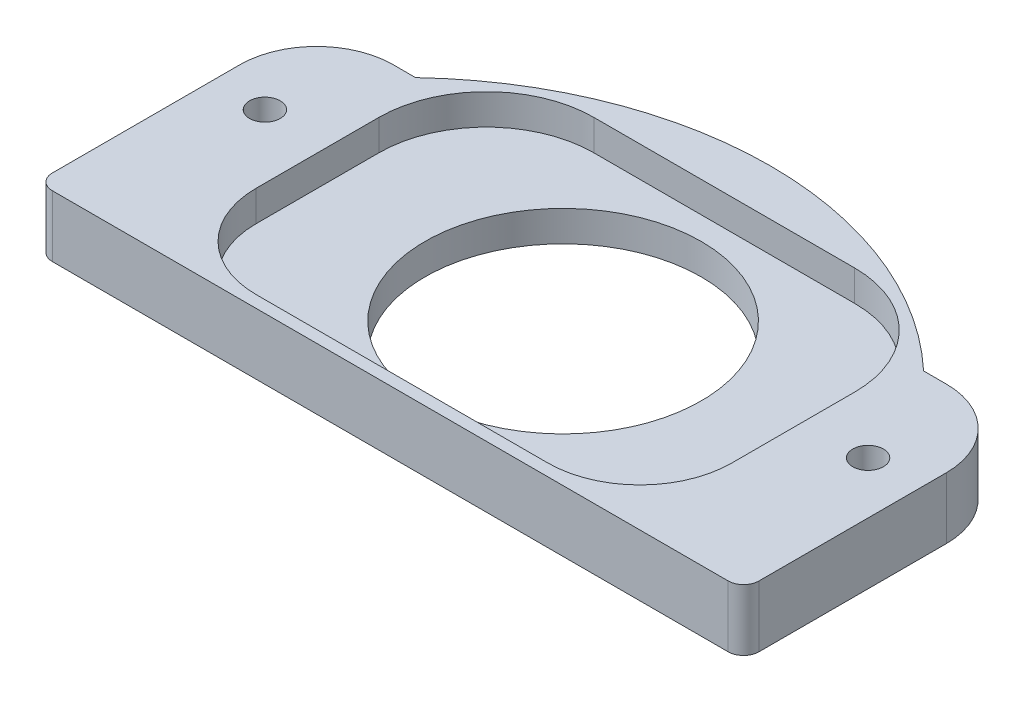
SolidWorks part; units mm, degrees
ref_plane "Front Plane" through (0, 0, 0) normal (0, 0, 1) x (1, 0, 0)
ref_plane "Top Plane" through (0, 0, 0) normal (0, 1, 0) x (1, 0, 0)
ref_plane "Right Plane" through (0, 0, 0) normal (1, 0, 0) x (0, 0, -1)
sketch "Sketch1" plane through (0, 0, 0) normal (0, 1, 0) x (1, 0, 0)
  line L0 (16.5494, 5.7) -> (18.0377, 5.7)
  line L2 (-23, 0.7) -> (-23, -11.5148)
  line L3 (-22, -12.5148) -> (22.0377, -12.5148)
  line L4 (23.0377, 0.7) -> (23.0377, -11.5148)
  line L5 (-23, -1.0148) -> (23, -1.0148) construction
  line L10 (-18, 5.7) -> (-16.5494, 5.7)
  circle A0 centre (0, -1.2352) radius 9
  circle A1 centre (19.65, -1.0148) radius 1
  circle A2 centre (-19.65, -1.0148) radius 1
  arc A3 (-18, 5.7) -> (-23, 0.7) centre (-18, 0.7) ccw
  arc A4 (16.5494, 5.7) -> (-16.5494, 5.7) centre (0, -11.8193) ccw
  arc A5 (23.0377, 0.7) -> (18.0377, 5.7) centre (18.0377, 0.7) ccw
  arc A6 (-22, -12.5148) -> (-23, -11.5148) centre (-22, -11.5148) cw
  arc A7 (23.0377, -11.5148) -> (22.0377, -12.5148) centre (22.0377, -11.5148) cw
  dimension "D3" = 1
  dimension "D5" = 11.5
  dimension "D1" = 5
  dimension "D2" = 5
  dimension "D4" = 1
extrude "Boss-Extrude1" add sketch "Sketch1" along normal blind 4 contours L2 A6 L3 A7 L4 A5 L0 A4 L10 A3
hole_wizard "Ø2.0mm Dowel Hole1" positions "Sketch3" profile "Sketch2" hole size "Ø2.0" standard "ANSI Metric" end condition through all
sketch "Sketch3" plane through (0, 4, 0) normal (0, 1, 0) x (1, 0, 0)
  point P0 (0, -1.2352)
sketch "Sketch2" plane through (0, 4, 1.2352) normal (1, 0, 0) x (0, 0, 1)
  line L0 (0, 0) -> (0, 4)
  line L1 (0, 4) -> (9, 4)
  line L2 (9, 4) -> (9, 0)
  line L5 (9, 0) -> (0, 0)
  line L11 (0, -6.35) -> (0, 107.95) construction
  dimension "Thru Hole Dia." = 18
  dimension "Thru Hole Depth" = 4
hole_wizard "Ø2.0mm Dowel Hole2" positions "Sketch5" profile "Sketch4" hole size "Ø2.0" standard "ANSI Metric"
sketch "Sketch5" plane through (0, 4, 0) normal (0, 1, 0) x (1, 0, 0)
  point P0 (-19.65, -1.0148)
  point P3 (19.65, -1.0148)
sketch "Sketch4" plane through (-19.65, 4, 1.0148) normal (1, 0, 0) x (0, 0, 1)
  line L0 (0, 0) -> (0, 10)
  line L1 (0, 10) -> (1, 10)
  line L2 (1, 10) -> (1, 0)
  line L5 (1, 0) -> (0, 0)
  line L10 (0, 10) -> (-1, 10) construction
  line L11 (0, -6.35) -> (0, 107.95) construction
  dimension "Hole Dia." = 2
  dimension "Hole Depth" = 10
  dimension "Drill Angle" = 180
sketch "Sketch9" plane through (0, 4, 0) normal (0, 1, 0) x (1, 0, 0)
  line L1 (-8.5, 9.2648) -> (8.5, 9.2648)
  line L2 (-15.5, 2.2648) -> (-15.5, -5.7352)
  line L3 (-9.5, -11.7352) -> (9.5, -11.7352)
  line L4 (15.5, 2.2648) -> (15.5, -5.7352)
  arc A0 (15.5, 2.2648) -> (8.5, 9.2648) centre (8.5, 2.2648) ccw
  arc A1 (-8.5, 9.2648) -> (-15.5, 2.2648) centre (-8.5, 2.2648) ccw
  arc A2 (15.5, -5.7352) -> (9.5, -11.7352) centre (9.5, -5.7352) cw
  arc A3 (-9.5, -11.7352) -> (-15.5, -5.7352) centre (-9.5, -5.7352) cw
  point P8 (15.5, 9.2648)
  point P11 (-15.5, 9.2648)
  point P16 (-15.5, -11.7352)
  dimension "D4" = 7
  dimension "D5" = 6
  dimension "D1" = 21
  dimension "D2" = 31
  dimension "D3" = 10.5
extrude "Cut-Extrude3" cut sketch "Sketch9" against normal blind 2
